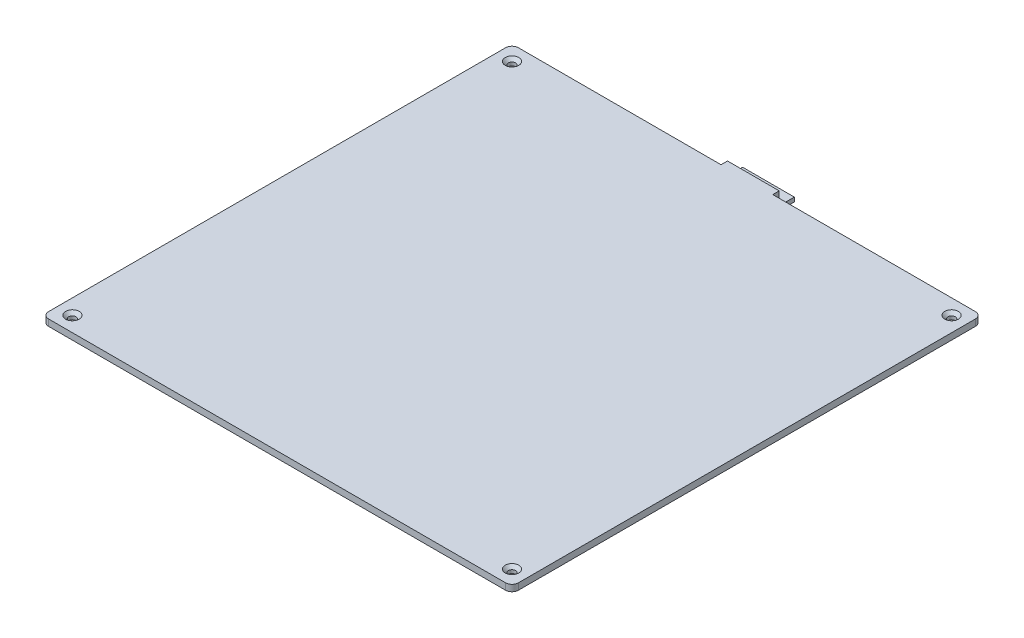
SolidWorks part; units mm, degrees
ref_plane "Front Plane" through (0, 0, 0) normal (0, 0, 1) x (1, 0, 0)
ref_plane "Top Plane" through (0, 0, 0) normal (0, 1, 0) x (1, 0, 0)
ref_plane "Right Plane" through (0, 0, 0) normal (1, 0, 0) x (0, 0, -1)
sketch "Sketch1" plane through (0, 0, 0) normal (0, 1, 0) x (1, 0, 0)
  line L1 (-106, 109) -> (106, 109)
  line L2 (-109, 106) -> (-109, -106)
  line L3 (-106, -109) -> (106, -109)
  line L4 (109, 106) -> (109, -106)
  line L5 (-109, 109) -> (109, -109) construction
  line L6 (-109, -109) -> (109, 109) construction
  arc A0 (-109, -106) -> (-106, -109) centre (-106, -106) ccw
  arc A1 (106, -109) -> (109, -106) centre (106, -106) ccw
  arc A2 (106, 109) -> (109, 106) centre (106, 106) cw
  arc A3 (-106, 109) -> (-109, 106) centre (-106, 106) ccw
  point P0 (0, 0)
  dimension "D3" = 3
  dimension "D1" = 218
  dimension "D2" = 218
extrude "Boss-Extrude1" add sketch "Sketch1" along normal blind 3
hole_wizard "CSK for M3 Flat Head Machine Screw1" positions "Sketch3" profile "Sketch4" countersink size "M3" standard "ANSI Metric" end condition through all
sketch "Sketch3" plane through (0, 3, 0) normal (0, 1, 0) x (1, 0, 0)
  line L2 (0, 135.2129) -> (0, -150.5896) construction
  line L4 (-149.8244, 0) -> (231.3195, 0) construction
  point P0 (-102, 102)
  point P16 (-102, -102)
  point P17 (102, -102)
  point P18 (102, 102)
  dimension "D1" = 102
  dimension "D2" = 102
sketch "Sketch4" plane through (-102, 3, -102) normal (1, 0, 0) x (0, 0, 1)
  line L0 (0, 0) -> (0, 3)
  line L1 (0, 3) -> (1.7, 3)
  line L2 (1.7, 3) -> (1.7, 1.45)
  line L3 (1.7, 1.45) -> (3.15, 0)
  line L5 (3.15, 0) -> (0, 0)
  line L6 (-1.7, 1.45) -> (-3.15, 0) construction
  line L11 (0, -6.35) -> (0, 107.95) construction
  dimension "Thru Hole Dia." = 3.4
  dimension "Thru Hole Depth" = 3
  dimension "Near C'Sink Dia." = 6.3
  dimension "Near C'Sink Angle" = 90
sketch "Sketch5" plane through (0, 0, 0) normal (0, -1, 0) x (-1, 0, 0)
  line L0 (0, 109) -> (12, 109)
  line L1 (-106, 109) -> (106, 109) construction
  line L2 (12, 109) -> (12, 119)
  line L3 (12, 119) -> (-12, 119)
  line L4 (-12, 119) -> (-12, 109)
  line L5 (-12, 109) -> (0, 109)
  dimension "D1" = 12
  dimension "D2" = 12
  dimension "D3" = 10
extrude "Boss-Extrude2" add sketch "Sketch5" along normal blind 8 from offset 3 offset against normal yes
sketch "Sketch6" plane through (0, 3, 0) normal (0, 1, 0) x (1, 0, 0)
  line L0 (-12, 112) -> (12, 112)
  line L1 (-12, 109) -> (-12, 119) construction
  line L2 (12, 119) -> (12, 109) construction
  line L3 (12, 112) -> (12, 119)
  line L4 (12, 119) -> (-12, 119)
  line L5 (-12, 119) -> (-12, 112)
  dimension "D1" = 7
extrude "Cut-Extrude1" cut sketch "Sketch6" against normal blind 6
